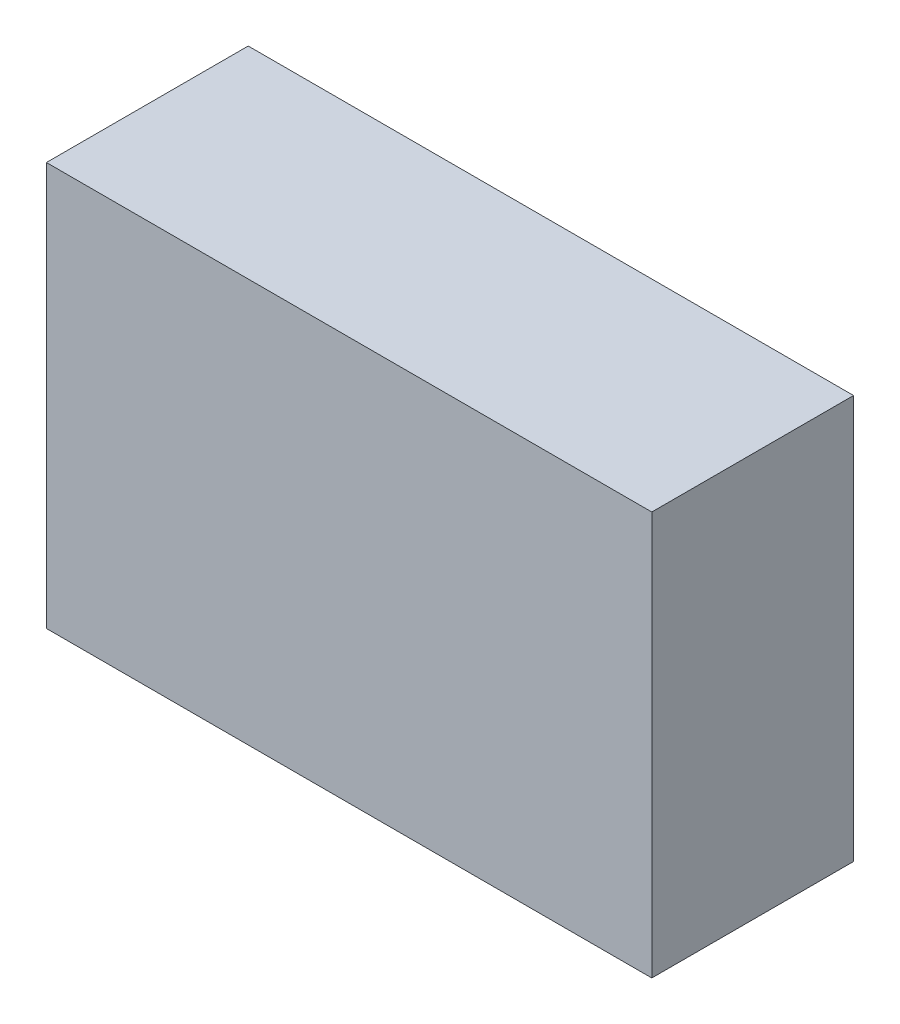
SolidWorks part; units mm, degrees
ref_plane "Plano frontal" through (0, 0, 0) normal (0, 0, 1) x (1, 0, 0)
ref_plane "Plano superior" through (0, 0, 0) normal (0, 1, 0) x (1, 0, 0)
ref_plane "Plano direito" through (0, 0, 0) normal (1, 0, 0) x (0, 0, -1)
sketch "Esboço1" plane through (0, 0, 0) normal (0, 0, 1) x (1, 0, 0)
  line L1 (-51.7922, 40.7559) -> (38.2078, 40.7559)
  line L2 (-51.7922, 40.7559) -> (-51.7922, -19.2441)
  line L3 (-51.7922, -19.2441) -> (38.2078, -19.2441)
  line L4 (38.2078, 40.7559) -> (38.2078, -19.2441)
extrude "Ressalto-extrusão1" add sketch "Esboço1" along normal blind 30
